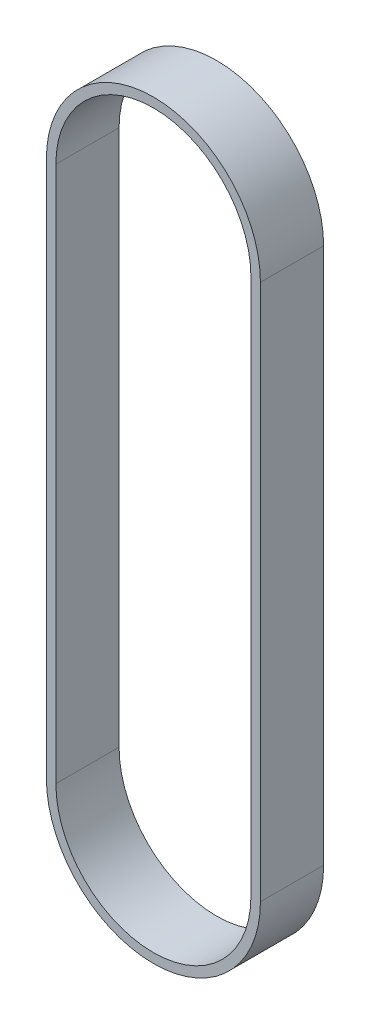
SolidWorks part; units mm, degrees
ref_plane "前视基准面" through (0, 0, 0) normal (0, 0, 1) x (1, 0, 0)
ref_plane "上视基准面" through (0, 0, 0) normal (0, 1, 0) x (1, 0, 0)
ref_plane "右视基准面" through (0, 0, 0) normal (1, 0, 0) x (0, 0, -1)
other "Configuration Table"
sketch "草图2" plane through (0, 0, 0) normal (0, 0, 1) x (1, 0, 0)
  line L0 (0, 0) -> (1, 0) construction
  line L1 (0, 0) -> (0, 1) construction
  line L2 (15.435, 0) -> (15.435, -84.9)
  line L3 (-15.435, -84.9) -> (-15.435, 0)
  arc A0 (-15.435, 0) -> (15.435, 0) centre (0, 0) cw
  arc A1 (15.435, -84.9) -> (-15.435, -84.9) centre (0, -84.9) cw
extrude "拉伸-薄壁1" add sketch "草图2" along normal mid plane 10 thin thin type one direction wall 1.5
